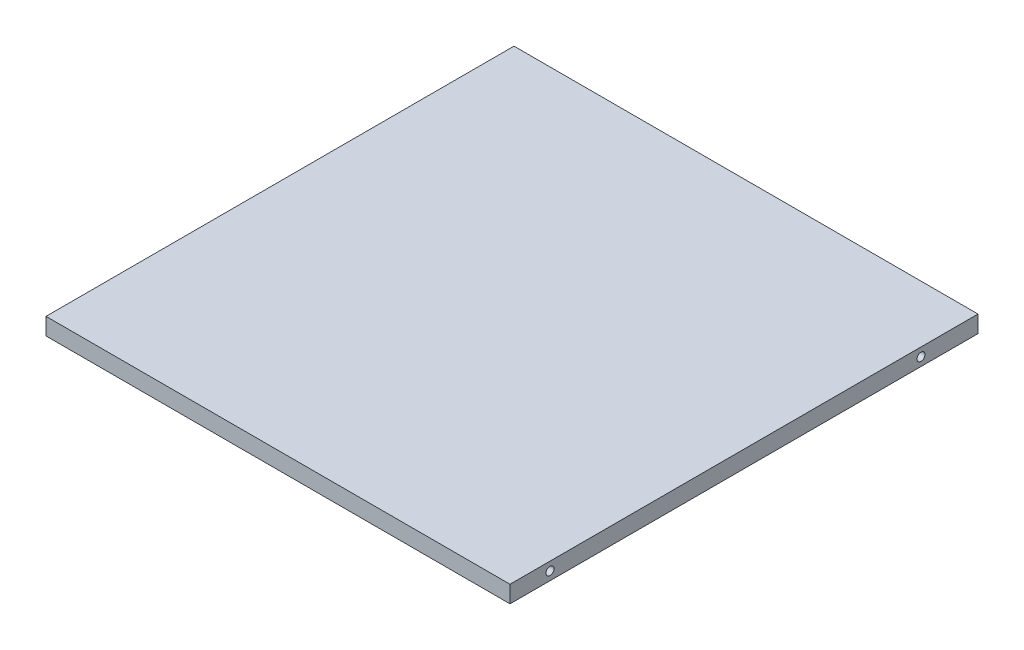
SolidWorks part; units mm, degrees
ref_plane "Front Plane" through (0, 0, 0) normal (0, 0, 1) x (1, 0, 0)
ref_plane "Top Plane" through (0, 0, 0) normal (0, 1, 0) x (1, 0, 0)
ref_plane "Right Plane" through (0, 0, 0) normal (1, 0, 0) x (0, 0, -1)
sketch "Sketch1" plane through (0, 0, 0) normal (0, 1, 0) x (1, 0, 0)
  line L1 (0, 0) -> (464, 0)
  line L2 (0, 0) -> (0, 468)
  line L3 (0, 468) -> (464, 468)
  line L4 (464, 0) -> (464, 468)
  dimension "D1" = 468
  dimension "D2" = 464
extrude "Boss-Extrude1" add sketch "Sketch1" along normal blind 17
sketch "Sketch2" plane through (0, 17, 0) normal (0, 1, 0) x (1, 0, 0)
  line L0 (232, 468) -> (232, 0) construction
  line L1 (464, 468) -> (0, 468) construction
  line L2 (0, 0) -> (464, 0) construction
sketch "Sketch3" plane through (464, 0, 0) normal (1, 0, 0) x (0, 0, -1)
  line L0 (0, 8.5) -> (468, 8.5) construction
  line L1 (0, 17) -> (0, 0) construction
  line L2 (468, 17) -> (468, 0) construction
  circle A0 centre (40, 8.5) radius 4
  circle A1 centre (411, 8.5) radius 4
  dimension "D1" = 2
  dimension "D2" = 40
  dimension "D3" = 57
extrude "Cut-Extrude1" cut sketch "Sketch3" against normal blind 25
sketch "Sketch4" plane through (0, 0, 0) normal (-1, 0, 0) x (0, 0, 1)
  line L0 (-468, 8.5) -> (0, 8.5) construction
  line L1 (-468, 17) -> (-468, 0) construction
  line L2 (0, 17) -> (0, 0) construction
  circle A0 centre (-411, 8.5) radius 4
  circle A1 centre (-40, 8.5) radius 4
  dimension "D1" = 2
  dimension "D3" = 40
  dimension "D2" = 57
extrude "Cut-Extrude2" cut sketch "Sketch4" against normal blind 25
